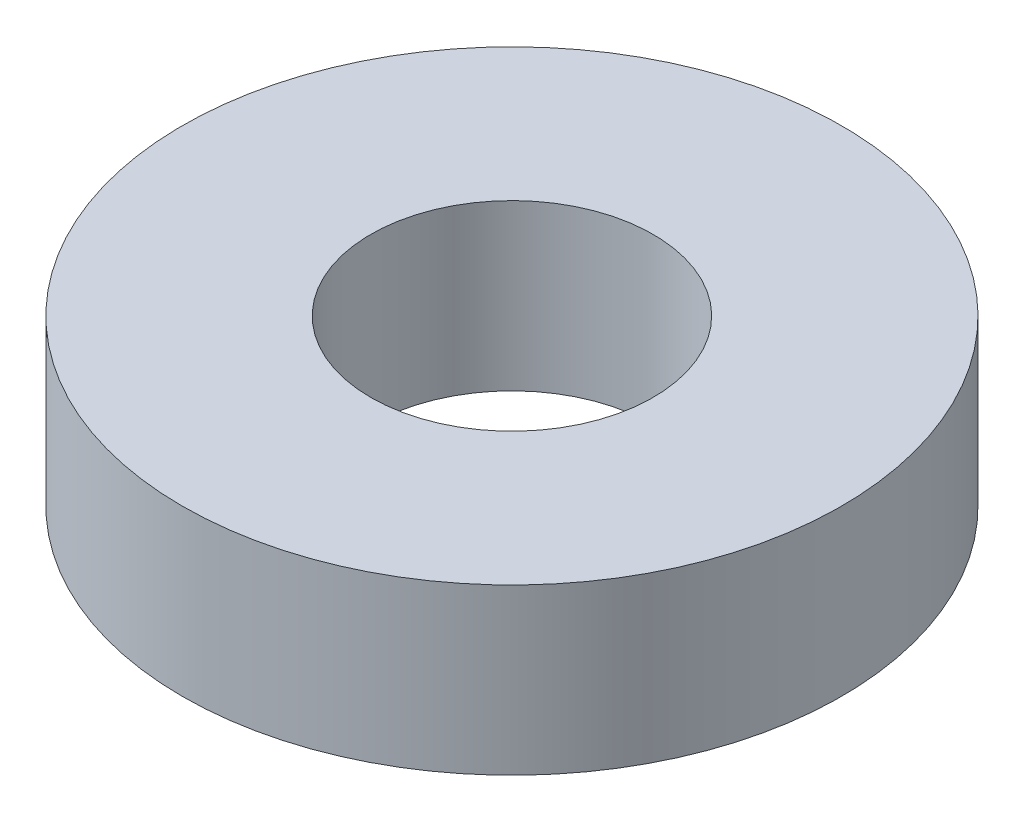
SolidWorks part; units mm, degrees
ref_plane "Front" through (0, 0, 0) normal (0, 0, 1) x (1, 0, 0)
ref_plane "Top" through (0, 0, 0) normal (0, 1, 0) x (1, 0, 0)
ref_plane "Right" through (0, 0, 0) normal (1, 0, 0) x (0, 0, -1)
sketch "草图1" plane through (0, 0, 0) normal (0, 1, 0) x (1, 0, 0)
  circle A0 centre (0, 0) radius 6
  circle A1 centre (0, 0) radius 14
  dimension "D1" = 12
  dimension "D2" = 28
extrude "凸台-拉伸1" add sketch "草图1" along normal blind 7
